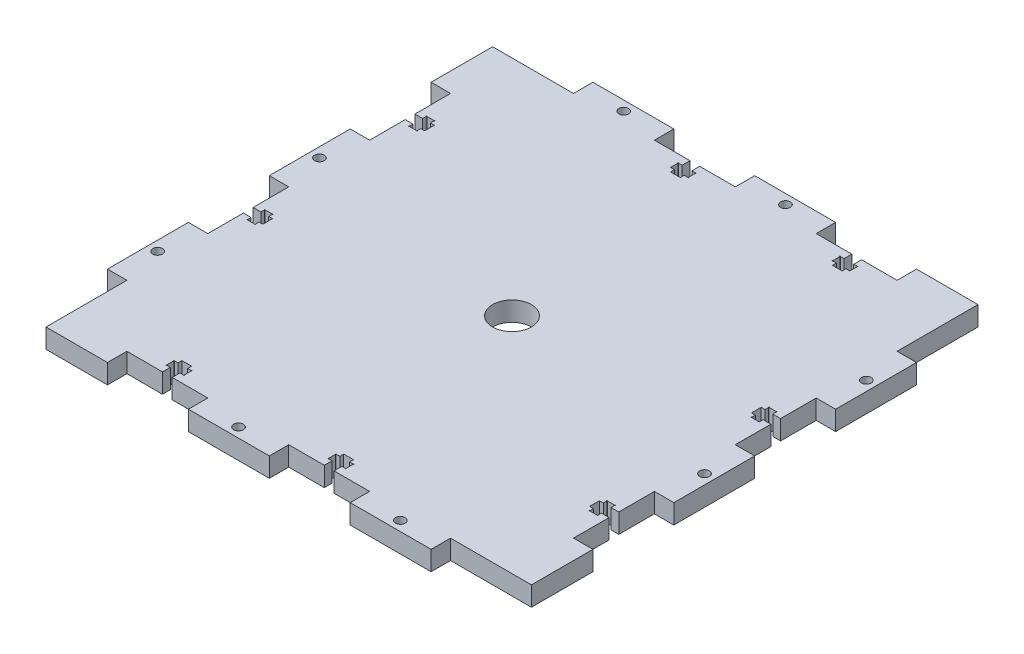
SolidWorks part; units mm, degrees
ref_plane "Front Plane" through (0, 0, 0) normal (0, 0, 1) x (1, 0, 0)
ref_plane "Top Plane" through (0, 0, 0) normal (0, 1, 0) x (1, 0, 0)
ref_plane "Right Plane" through (0, 0, 0) normal (1, 0, 0) x (0, 0, -1)
sketch "Sketch1" plane through (0, 0, 0) normal (0, 1, 0) x (1, 0, 0)
  line L0 (0, 75) -> (25, 75)
  line L1 (-50, 75) -> (-25, 75)
  line L2 (-75, 69) -> (-75, 50)
  line L3 (-69, -75) -> (-50, -75)
  line L4 (75, 50) -> (75, 25)
  line L7 (-75, 69) -> (-50, 69)
  line L8 (-50, 75) -> (-50, 69)
  line L10 (-25, 75) -> (-25, 69)
  line L11 (-25, 69) -> (0, 69)
  line L12 (0, 75) -> (0, 69)
  line L13 (50, 75) -> (69, 75)
  line L15 (25, 75) -> (25, 69)
  line L16 (25, 69) -> (50, 69)
  line L17 (50, 75) -> (50, 69)
  line L18 (75, 0) -> (75, -25)
  line L21 (75, 50) -> (69, 50)
  line L22 (69, 75) -> (69, 50)
  line L23 (75, 25) -> (69, 25)
  line L25 (75, 0) -> (69, 0)
  line L26 (69, 25) -> (69, 0)
  line L27 (75, -25) -> (69, -25)
  line L29 (75, -50) -> (69, -50)
  line L30 (69, -25) -> (69, -50)
  line L31 (75, -50) -> (75, -69)
  line L32 (25, -75) -> (50, -75)
  line L35 (75, -69) -> (50, -69)
  line L36 (50, -75) -> (50, -69)
  line L38 (25, -75) -> (25, -69)
  line L39 (25, -69) -> (0, -69)
  line L40 (0, -75) -> (0, -69)
  line L42 (-25, -75) -> (-25, -69)
  line L43 (-25, -69) -> (-50, -69)
  line L44 (-50, -75) -> (-50, -69)
  line L45 (-25, -75) -> (0, -75)
  line L46 (-75, 25) -> (-75, 0)
  line L49 (-75, -50) -> (-69, -50)
  line L50 (-69, -75) -> (-69, -50)
  line L51 (-75, -25) -> (-69, -25)
  line L53 (-75, 0) -> (-69, 0)
  line L54 (-69, -25) -> (-69, 0)
  line L55 (-75, 25) -> (-69, 25)
  line L57 (-75, 50) -> (-69, 50)
  line L58 (-69, 25) -> (-69, 50)
  line L59 (-75, -25) -> (-75, -50)
  dimension "D1" = 150
  dimension "D2" = 150
  dimension "D3" = 25
  dimension "D4" = 6
  dimension "D5" = 25
  dimension "25" = 25
  dimension "D6" = 25
  dimension "D7" = 6
  dimension "D8" = 6
  dimension "D9" = 25
  dimension "D10" = 25
  dimension "D11" = 6
  dimension "D12" = 25
  dimension "D13" = 6
  dimension "D14" = 25
  dimension "D15" = 25
  dimension "D16" = 6
  dimension "D17" = 25
  dimension "D18" = 19
  dimension "D19" = 6
  dimension "D20" = 25
  dimension "D21" = 25
  dimension "D22" = 25
  dimension "D23" = 6
  dimension "D24" = 6
  dimension "D25" = 25
  dimension "D26" = 25
  dimension "D27" = 19
  dimension "D28" = 6
  dimension "D29" = 25
  dimension "D30" = 25
  dimension "D31" = 6
  dimension "D32" = 25
  dimension "D33" = 25
  dimension "D34" = 6
  dimension "D35" = 25
  dimension "D36" = 19
extrude "Boss-Extrude1" add sketch "Sketch1" along normal blind 6
sketch "Sketch2" plane through (0, 6, 0) normal (0, 1, 0) x (1, 0, 0)
  line L0 (-25, 75) -> (-50, 75) construction
  line L1 (-25, 69) -> (-25, 75) construction
  line L2 (25, 75) -> (0, 75) construction
  line L3 (25, 69) -> (25, 75) construction
  line L4 (75, 25) -> (75, 50) construction
  line L5 (75, 50) -> (69, 50) construction
  line L6 (75, -25) -> (75, 0) construction
  line L7 (75, 0) -> (69, 0) construction
  line L8 (25, -75) -> (50, -75) construction
  line L9 (50, -75) -> (50, -69) construction
  line L10 (-25, -75) -> (0, -75) construction
  line L11 (0, -75) -> (0, -69) construction
  line L12 (-69, -25) -> (-75, -25) construction
  line L13 (-75, -25) -> (-75, -50) construction
  line L14 (-75, 25) -> (-75, 0) construction
  line L15 (-75, 0) -> (-69, 0) construction
  line L16 (-11, 69) -> (-14, 69)
  line L59 (0, 69) -> (-25, 69) construction
  line L60 (-14, 69) -> (-14, 66.6)
  line L61 (-14, 66.6) -> (-15.1, 66.6)
  line L63 (-15.2, 66.5) -> (-15.2, 64.3)
  line L65 (-15.1, 64.2) -> (-14, 64.2)
  line L66 (-14, 64.2) -> (-14, 63)
  line L67 (-14, 63) -> (-11, 63)
  line L69 (-12.5, 69) -> (-12.5, 63) construction
  line L72 (-11, 64.2) -> (-11, 63)
  line L73 (-9.9, 64.2) -> (-11, 64.2)
  line L74 (-9.8, 66.5) -> (-9.8, 64.3)
  line L75 (-11, 66.6) -> (-9.9, 66.6)
  line L76 (-11, 69) -> (-11, 66.6)
  line L91 (69, 11) -> (69, 14)
  line L92 (69, 14) -> (66.6, 14)
  line L93 (66.6, 14) -> (66.6, 15.1)
  line L94 (66.5, 15.2) -> (64.3, 15.2)
  line L95 (64.2, 15.1) -> (64.2, 14)
  line L96 (64.2, 14) -> (63, 14)
  line L97 (63, 14) -> (63, 11)
  line L98 (69, 12.5) -> (63, 12.5) construction
  line L99 (64.2, 11) -> (63, 11)
  line L100 (64.2, 9.9) -> (64.2, 11)
  line L101 (66.5, 9.8) -> (64.3, 9.8)
  line L102 (66.6, 11) -> (66.6, 9.9)
  line L103 (69, 11) -> (66.6, 11)
  line L104 (69, 0) -> (69, 25) construction
  line L105 (39, 69) -> (36, 69)
  line L106 (36, 69) -> (36, 66.6)
  line L107 (36, 66.6) -> (34.9, 66.6)
  line L108 (34.8, 66.5) -> (34.8, 64.3)
  line L109 (34.9, 64.2) -> (36, 64.2)
  line L110 (36, 64.2) -> (36, 63)
  line L111 (36, 63) -> (39, 63)
  line L112 (37.5, 69) -> (37.5, 63) construction
  line L113 (39, 64.2) -> (39, 63)
  line L114 (40.1, 64.2) -> (39, 64.2)
  line L115 (40.2, 66.5) -> (40.2, 64.3)
  line L116 (39, 66.6) -> (40.1, 66.6)
  line L117 (39, 69) -> (39, 66.6)
  line L118 (50, 69) -> (25, 69) construction
  line L119 (69, -39) -> (69, -36)
  line L120 (69, -36) -> (66.6, -36)
  line L121 (66.6, -36) -> (66.6, -34.9)
  line L122 (66.5, -34.8) -> (64.3, -34.8)
  line L123 (64.2, -34.9) -> (64.2, -36)
  line L124 (64.2, -36) -> (63, -36)
  line L125 (63, -36) -> (63, -39)
  line L126 (69, -37.5) -> (63, -37.5) construction
  line L127 (64.2, -39) -> (63, -39)
  line L128 (64.2, -40.1) -> (64.2, -39)
  line L129 (66.5, -40.2) -> (64.3, -40.2)
  line L130 (66.6, -39) -> (66.6, -40.1)
  line L131 (69, -39) -> (66.6, -39)
  line L132 (69, -50) -> (69, -25) construction
  line L133 (11, -69) -> (14, -69)
  line L134 (14, -69) -> (14, -66.6)
  line L135 (14, -66.6) -> (15.1, -66.6)
  line L136 (15.2, -66.5) -> (15.2, -64.3)
  line L137 (15.1, -64.2) -> (14, -64.2)
  line L138 (14, -64.2) -> (14, -63)
  line L139 (14, -63) -> (11, -63)
  line L140 (12.5, -69) -> (12.5, -63) construction
  line L141 (11, -64.2) -> (11, -63)
  line L142 (9.9, -64.2) -> (11, -64.2)
  line L143 (9.8, -66.5) -> (9.8, -64.3)
  line L144 (11, -66.6) -> (9.9, -66.6)
  line L145 (11, -69) -> (11, -66.6)
  line L146 (0, -69) -> (25, -69) construction
  line L147 (-39, -69) -> (-36, -69)
  line L148 (-36, -69) -> (-36, -66.6)
  line L149 (-36, -66.6) -> (-34.9, -66.6)
  line L150 (-34.8, -66.5) -> (-34.8, -64.3)
  line L151 (-34.9, -64.2) -> (-36, -64.2)
  line L152 (-36, -64.2) -> (-36, -63)
  line L153 (-36, -63) -> (-39, -63)
  line L154 (-37.5, -69) -> (-37.5, -63) construction
  line L155 (-39, -64.2) -> (-39, -63)
  line L156 (-40.1, -64.2) -> (-39, -64.2)
  line L157 (-40.2, -66.5) -> (-40.2, -64.3)
  line L158 (-39, -66.6) -> (-40.1, -66.6)
  line L159 (-39, -69) -> (-39, -66.6)
  line L160 (-50, -69) -> (-25, -69) construction
  line L161 (-69, 39) -> (-69, 36)
  line L162 (-69, 36) -> (-66.6, 36)
  line L163 (-66.6, 36) -> (-66.6, 34.9)
  line L164 (-66.5, 34.8) -> (-64.3, 34.8)
  line L165 (-64.2, 34.9) -> (-64.2, 36)
  line L166 (-64.2, 36) -> (-63, 36)
  line L167 (-63, 36) -> (-63, 39)
  line L168 (-69, 37.5) -> (-63, 37.5) construction
  line L169 (-64.2, 39) -> (-63, 39)
  line L170 (-64.2, 40.1) -> (-64.2, 39)
  line L171 (-66.5, 40.2) -> (-64.3, 40.2)
  line L172 (-66.6, 39) -> (-66.6, 40.1)
  line L173 (-69, 39) -> (-66.6, 39)
  line L174 (-69, 50) -> (-69, 25) construction
  line L175 (-69, -11) -> (-69, -14)
  line L176 (-69, -14) -> (-66.6, -14)
  line L177 (-66.6, -14) -> (-66.6, -15.1)
  line L178 (-66.5, -15.2) -> (-64.3, -15.2)
  line L179 (-64.2, -15.1) -> (-64.2, -14)
  line L180 (-64.2, -14) -> (-63, -14)
  line L181 (-63, -14) -> (-63, -11)
  line L182 (-69, -12.5) -> (-63, -12.5) construction
  line L183 (-64.2, -11) -> (-63, -11)
  line L184 (-64.2, -9.9) -> (-64.2, -11)
  line L185 (-66.5, -9.8) -> (-64.3, -9.8)
  line L186 (-66.6, -11) -> (-66.6, -9.9)
  line L187 (-69, -11) -> (-66.6, -11)
  line L188 (-69, 0) -> (-69, -25) construction
  circle A0 centre (-37.5, 72) radius 1.5
  circle A1 centre (12.5, 72) radius 1.5
  circle A2 centre (72, 37.5) radius 1.5
  circle A3 centre (72, -12.5) radius 1.5
  circle A4 centre (37.5, -72) radius 1.5
  circle A5 centre (-12.5, -72) radius 1.5
  circle A6 centre (-72, -37.5) radius 1.5
  circle A7 centre (-72, 12.5) radius 1.5
  arc A9 (-15.1, 66.6) -> (-15.2, 66.5) centre (-15.2, 66.6) ccw
  arc A10 (-15.2, 64.3) -> (-15.1, 64.2) centre (-15.2, 64.2) ccw
  arc A11 (-9.8, 64.3) -> (-9.9, 64.2) centre (-9.8, 64.2) cw
  arc A12 (-9.9, 66.6) -> (-9.8, 66.5) centre (-9.8, 66.6) cw
  arc A17 (66.6, 15.1) -> (66.5, 15.2) centre (66.6, 15.2) ccw
  arc A18 (64.3, 15.2) -> (64.2, 15.1) centre (64.2, 15.2) ccw
  arc A19 (64.3, 9.8) -> (64.2, 9.9) centre (64.2, 9.8) cw
  arc A20 (66.6, 9.9) -> (66.5, 9.8) centre (66.6, 9.8) cw
  arc A21 (34.9, 66.6) -> (34.8, 66.5) centre (34.8, 66.6) ccw
  arc A22 (34.8, 64.3) -> (34.9, 64.2) centre (34.8, 64.2) ccw
  arc A23 (40.2, 64.3) -> (40.1, 64.2) centre (40.2, 64.2) cw
  arc A24 (40.1, 66.6) -> (40.2, 66.5) centre (40.2, 66.6) cw
  arc A25 (66.6, -34.9) -> (66.5, -34.8) centre (66.6, -34.8) ccw
  arc A26 (64.3, -34.8) -> (64.2, -34.9) centre (64.2, -34.8) ccw
  arc A27 (64.3, -40.2) -> (64.2, -40.1) centre (64.2, -40.2) cw
  arc A28 (66.6, -40.1) -> (66.5, -40.2) centre (66.6, -40.2) cw
  arc A29 (15.1, -66.6) -> (15.2, -66.5) centre (15.2, -66.6) ccw
  arc A30 (15.2, -64.3) -> (15.1, -64.2) centre (15.2, -64.2) ccw
  arc A31 (9.8, -64.3) -> (9.9, -64.2) centre (9.8, -64.2) cw
  arc A32 (9.9, -66.6) -> (9.8, -66.5) centre (9.8, -66.6) cw
  arc A33 (-34.9, -66.6) -> (-34.8, -66.5) centre (-34.8, -66.6) ccw
  arc A34 (-34.8, -64.3) -> (-34.9, -64.2) centre (-34.8, -64.2) ccw
  arc A35 (-40.2, -64.3) -> (-40.1, -64.2) centre (-40.2, -64.2) cw
  arc A36 (-40.1, -66.6) -> (-40.2, -66.5) centre (-40.2, -66.6) cw
  arc A37 (-66.6, 34.9) -> (-66.5, 34.8) centre (-66.6, 34.8) ccw
  arc A38 (-64.3, 34.8) -> (-64.2, 34.9) centre (-64.2, 34.8) ccw
  arc A39 (-64.3, 40.2) -> (-64.2, 40.1) centre (-64.2, 40.2) cw
  arc A40 (-66.6, 40.1) -> (-66.5, 40.2) centre (-66.6, 40.2) cw
  arc A41 (-66.6, -15.1) -> (-66.5, -15.2) centre (-66.6, -15.2) ccw
  arc A42 (-64.3, -15.2) -> (-64.2, -15.1) centre (-64.2, -15.2) ccw
  arc A43 (-64.3, -9.8) -> (-64.2, -9.9) centre (-64.2, -9.8) cw
  arc A44 (-66.6, -9.9) -> (-66.5, -9.8) centre (-66.6, -9.8) cw
  point P83 (-12.5, 69)
  point P104 (69, 12.5)
  point P122 (37.5, 69)
  point P148 (69, -37.5)
  point P174 (12.5, -69)
  point P196 (-37.5, -69)
  point P222 (-69, 37.5)
  point P246 (-69, -12.5)
  dimension "D1" = 3
  dimension "D3" = 3
  dimension "D5" = 3
  dimension "D7" = 3
  dimension "D9" = 3
  dimension "D11" = 3
  dimension "D13" = 12.5
  dimension "D15" = 3
  dimension "D32" = 3
  dimension "D31" = 3
  dimension "D17" = 3
  dimension "D29" = 3
  dimension "D30" = 3
  dimension "D33" = 3
  dimension "D34" = 3
  dimension "D35" = 3
  dimension "D36" = 3
  dimension "D2" = 12.5
  dimension "D4" = 12.5
  dimension "D6" = 12.5
  dimension "D8" = 12.5
  dimension "D10" = 12.5
  dimension "D12" = 12.5
  dimension "D14" = 3
  dimension "D16" = 12.5
  dimension "D18" = 6
  dimension "D19" = 5.4
  dimension "D20" = 2.4
  dimension "D21" = 1.2
  dimension "D22" = 0.1
  dimension "D23" = 3
  dimension "D24" = 6
  dimension "D25" = 5.4
  dimension "D26" = 2.4
  dimension "D27" = 1.2
  dimension "D28" = 0.1
  dimension "D37" = 3
  dimension "D38" = 6
  dimension "D39" = 5.4
  dimension "D40" = 2.4
  dimension "D41" = 1.2
  dimension "D42" = 0.1
  dimension "D43" = 3
  dimension "D44" = 6
  dimension "D45" = 5.4
  dimension "D46" = 2.4
  dimension "D47" = 1.2
  dimension "D48" = 0.1
  dimension "D49" = 3
  dimension "D50" = 6
  dimension "D51" = 5.4
  dimension "D52" = 2.4
  dimension "D53" = 1.2
  dimension "D54" = 0.1
  dimension "D55" = 3
  dimension "D56" = 6
  dimension "D57" = 5.4
  dimension "D58" = 2.4
  dimension "D59" = 1.2
  dimension "D60" = 0.1
  dimension "D61" = 3
  dimension "D62" = 6
  dimension "D63" = 5.4
  dimension "D64" = 2.4
  dimension "D65" = 1.2
  dimension "D66" = 0.1
  dimension "D67" = 3
  dimension "D68" = 6
  dimension "D69" = 5.4
  dimension "D70" = 2.4
  dimension "D71" = 1.2
  dimension "D72" = 0.1
extrude "Cut-Extrude1" cut sketch "Sketch2" against normal through all
sketch "Sketch3" plane through (0, 0, 0) normal (0, -1, 0) x (1, 0, 0)
  circle A0 centre (0, 0) radius 6
  dimension "D1" = 12
extrude "Cut-Extrude2" cut sketch "Sketch3" against normal through all
